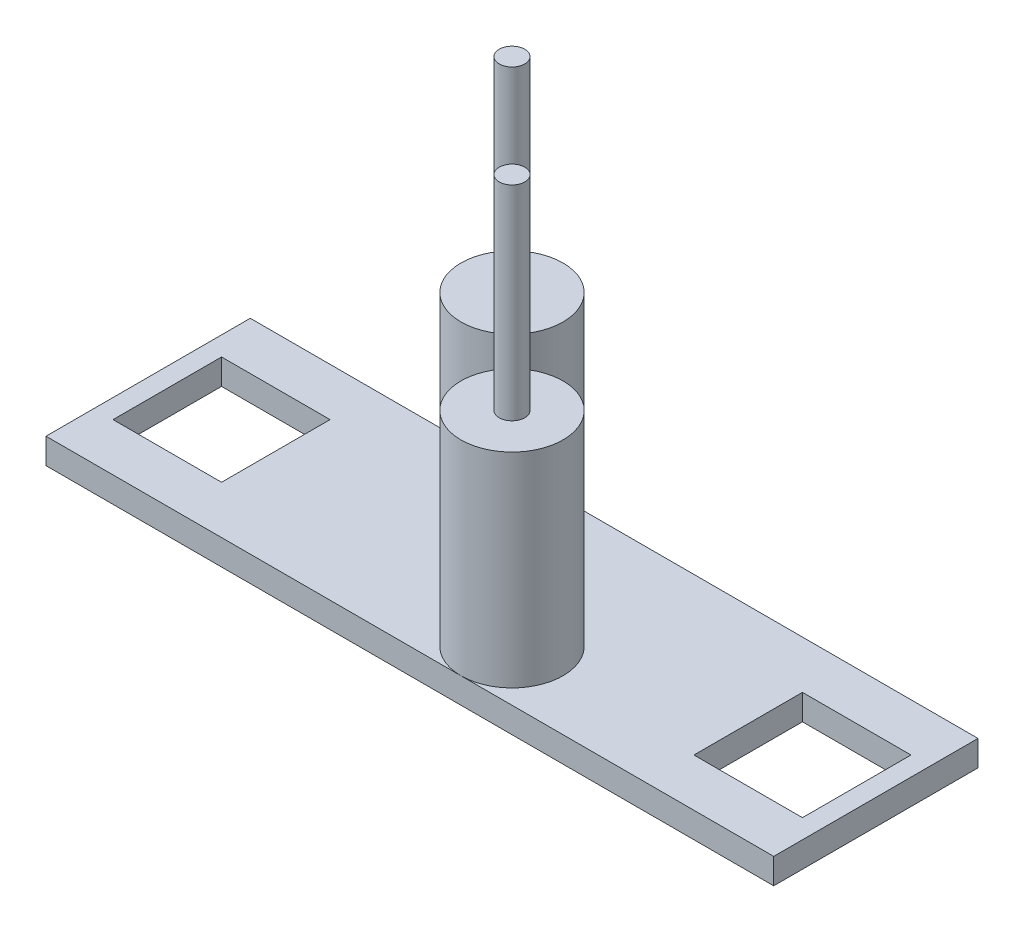
SolidWorks part; units mm, degrees
ref_plane "Front Plane" through (0, 0, 0) normal (0, 0, 1) x (1, 0, 0)
ref_plane "Top Plane" through (0, 0, 0) normal (0, 1, 0) x (1, 0, 0)
ref_plane "Right Plane" through (0, 0, 0) normal (1, 0, 0) x (0, 0, -1)
sketch "Sketch1" plane through (0, 0, 0) normal (0, 1, 0) x (1, 0, 0)
  line L1 (0, 0) -> (-180.975, 0)
  line L2 (0, 0) -> (0, -50.8)
  line L3 (0, -50.8) -> (-180.975, -50.8)
  line L4 (-180.975, 0) -> (-180.975, -50.8)
  line L5 (-176.2125, -11.9062) -> (-149.225, -11.9062)
  line L6 (-176.2125, -11.9062) -> (-176.2125, -38.8937)
  line L7 (-176.2125, -38.8937) -> (-149.225, -38.8937)
  line L8 (-149.225, -11.9062) -> (-149.225, -38.8937)
  line L9 (-4.7625, -11.9063) -> (-31.75, -11.9062)
  line L10 (-4.7625, -11.9063) -> (-4.7625, -38.8937)
  line L11 (-4.7625, -38.8937) -> (-31.75, -38.8937)
  line L12 (-31.75, -11.9062) -> (-31.75, -38.8937)
  point P9 (-176.2125, -25.4)
  point P10 (-180.975, -25.4)
  point P15 (-4.7625, -25.4)
  point P16 (0, -25.4)
  point P17 (0, 0)
  dimension "D1" = 180.975
  dimension "D2" = 50.8
  dimension "D3" = 26.9875
  dimension "D4" = 26.9875
  dimension "D5" = 31.75
  dimension "D6" = 26.9875
  dimension "D7" = 26.9875
  dimension "D8" = 31.75
extrude "Boss-Extrude1" add sketch "Sketch1" along normal blind 6.35 contours L1 L4 L3 L2 | L8 L7 L6 L5 | L12 L11 L10 L9
sketch "Sketch3" plane through (0, 6.35, 0) normal (0, 1, 0) x (1, 0, 0)
  line L0 (0, 0) -> (-180.975, 0) construction
  line L1 (-146.05, 0) -> (-34.925, 0)
  line L2 (-146.05, 0) -> (-146.05, -50.8)
  line L3 (-146.05, -50.8) -> (-34.925, -50.8)
  line L4 (-34.925, 0) -> (-34.925, -50.8)
  line L5 (0, -50.8) -> (-180.975, -50.8) construction
  line L6 (0, -50.8) -> (-180.975, -50.8) construction
  circle A0 centre (-77.7875, -38.1) radius 3.175
  circle A1 centre (-103.1875, -12.7) radius 3.175
  point P8 (-90.4875, 0)
  point P11 (-90.4875, -50.8)
  dimension "D3" = 12.7
  dimension "D1" = 111.125
  dimension "D2" = 0
  dimension "D4" = 42.8625
  dimension "D5" = 12.7
  dimension "D6" = 42.8625
extrude "Boss-Extrude2" add sketch "Sketch3" along normal blind 101.6 contours A0 | A1
sketch "Sketch4" plane through (0, 6.35, 0) normal (0, 1, 0) x (1, 0, 0)
  circle A0 centre (-103.1875, -12.7) radius 12.7
  circle A1 centre (-77.7875, -38.1) radius 12.7
extrude "Boss-Extrude3" add sketch "Sketch4" along normal blind 50.8
